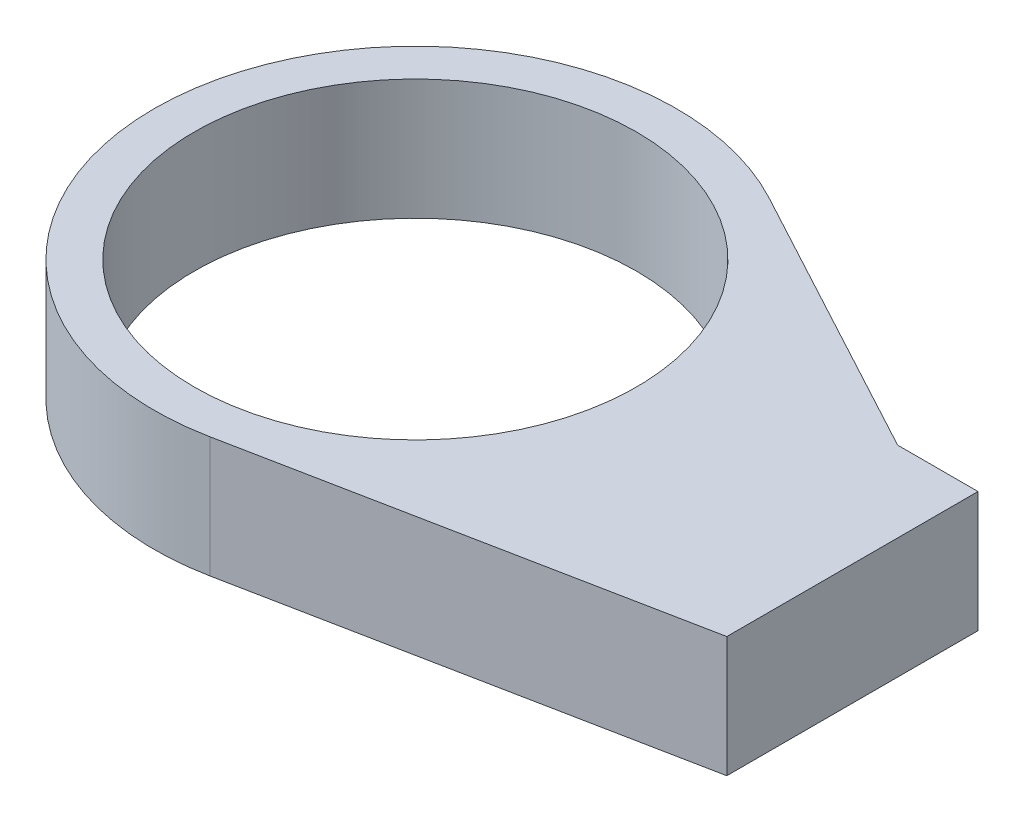
SolidWorks part; units mm, degrees
ref_plane "Front Plane" through (0, 0, 0) normal (0, 0, 1) x (1, 0, 0)
ref_plane "Top Plane" through (0, 0, 0) normal (0, 1, 0) x (1, 0, 0)
ref_plane "Right Plane" through (0, 0, 0) normal (1, 0, 0) x (0, 0, -1)
sketch "Sketch1" plane through (0, 0, 0) normal (0, 1, 0) x (1, 0, 0)
  line L1 (48, 8) -> (40, 8)
  line L2 (48, 8) -> (48, -17)
  line L3 (40, 8) -> (12.3209, 22.8953)
  line L4 (48, -17) -> (5.0504, -25.5048)
  circle A0 centre (0, 0) radius 22
  arc A1 (12.3209, 22.8953) -> (5.0504, -25.5048) centre (0, 0) ccw
  dimension "D1" = 26
  dimension "D2" = 44
  dimension "D3" = 8
  dimension "D4" = 8
  dimension "D5" = 48
  dimension "D6" = 25
extrude "Boss-Extrude1" add sketch "Sketch1" along normal blind 12
